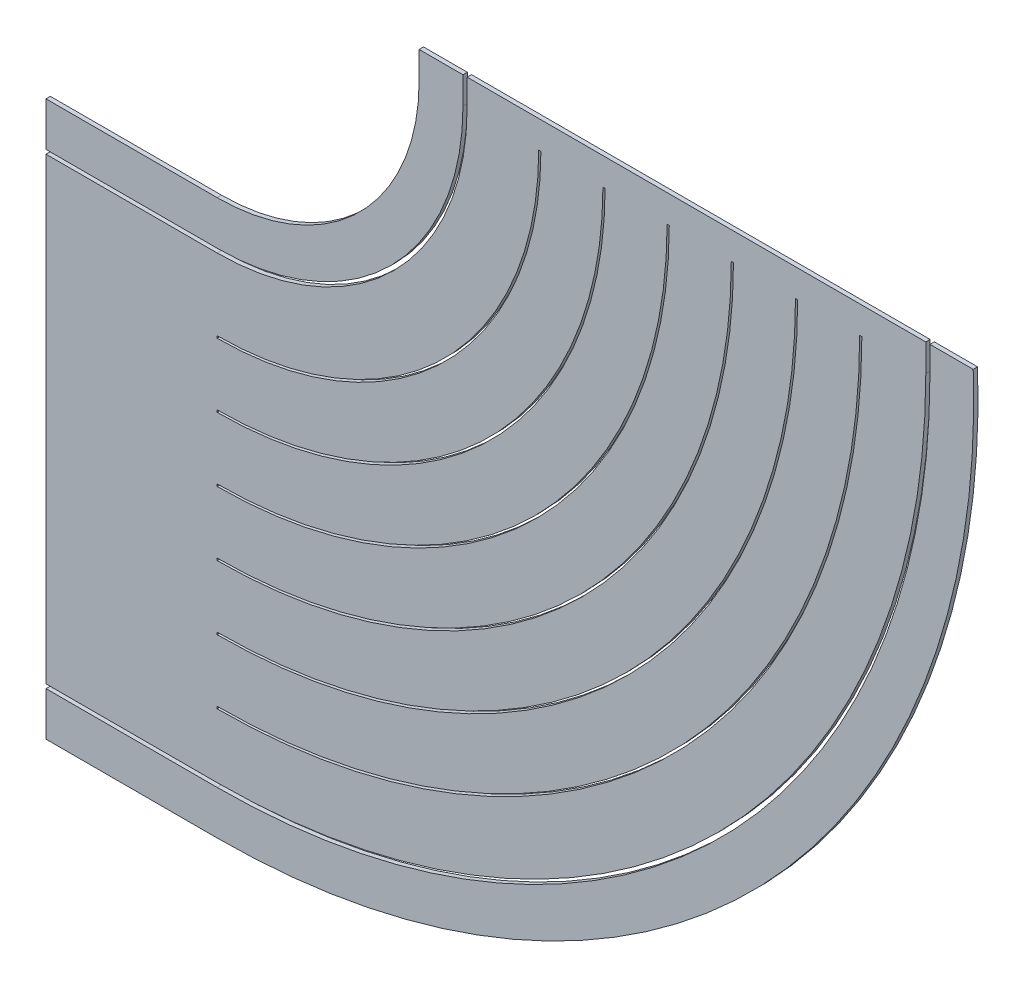
SolidWorks part; units mm, degrees
ref_plane "Front Plane" through (0, 0, 0) normal (0, 0, 1) x (1, 0, 0)
ref_plane "Top Plane" through (0, 0, 0) normal (0, 1, 0) x (1, 0, 0)
ref_plane "Right Plane" through (0, 0, 0) normal (1, 0, 0) x (0, 0, -1)
sketch "Sketch1" plane through (0, 0, 0) normal (0, 0, 1) x (1, 0, 0)
  line L2 (1495, -4410) -> (2304.2758, -4410)
  line L3 (1200, -4745) -> (950, -4745)
  line L4 (2302.7806, -4380) -> (1486.5746, -4380)
  line L5 (1130, -4736.5746) -> (1130, -5552.7806)
  line L8 (1495, -4450) -> (1495, -4410)
  line L10 (950, -5555) -> (950, -4745)
  line L12 (950, -4815) -> (950, -4809) construction
  line L17 (1565, -4410) -> (1559, -4410)
  line L18 (1200, -4809) -> (950, -4809)
  line L19 (950, -4809) -> (950, -4815)
  line L20 (950, -4815) -> (1200, -4815)
  line L21 (1565, -4410) -> (1559, -4410)
  line L22 (1200, -4809) -> (950, -4809)
  line L23 (950, -4809) -> (950, -4815)
  line L24 (950, -4815) -> (1200, -4815)
  line L47 (1565, -4450) -> (1565, -4410)
  line L48 (1565, -4450) -> (1565, -4410)
  line L49 (1559, -4410) -> (1559, -4450)
  line L50 (1559, -4410) -> (1559, -4450)
  line L183 (1200, -5555) -> (950, -5555)
  line L660 (1200, -4919.65) -> (1200, -4922.85)
  line L661 (1200, -5013.4) -> (1200, -5016.6)
  line L662 (1200, -5107.15) -> (1200, -5110.35)
  line L663 (1200, -5200.9) -> (1200, -5204.1)
  line L664 (1200, -5294.65) -> (1200, -5297.85)
  line L665 (1200, -5388.4) -> (1200, -5391.6)
  line L666 (1668.75, -4450) -> (2142.5, -4450)
  line L959 (1200, -5485) -> (950, -5485) construction
  line L960 (1200, -5491) -> (950, -5491) construction
  line L961 (1200, -5485) -> (950, -5485)
  line L962 (1200, -5491) -> (950, -5491)
  line L963 (2235, -4450) -> (2235, -4410)
  line L964 (2235, -4410) -> (2241, -4410)
  line L965 (2241, -4410) -> (2241, -4450)
  arc A2 (1200, -4745) -> (1495, -4450) centre (1200, -4450) ccw
  arc A4 (1130, -5552.7806) -> (2302.7806, -4380) centre (1200, -4450) ccw
  arc A5 (1130, -4736.5746) -> (1486.5746, -4380) centre (1200, -4450) ccw
  arc A6 (1200, -5555) -> (2304.2758, -4410) centre (1200, -4450) ccw
  arc A7 (1200, -4745) -> (1495, -4450) centre (1200, -4450) ccw
  arc A9 (1200, -4815) -> (1565, -4450) centre (1200, -4450) ccw
  arc A10 (1200, -4809) -> (1559, -4450) centre (1200, -4450) ccw
  arc A11 (1200, -4815) -> (1565, -4450) centre (1200, -4450) ccw
  arc A12 (1200, -4809) -> (1559, -4450) centre (1200, -4450) ccw
  arc A149 (1200, -5392.5) -> (2142.5, -4450) centre (1200, -4450) ccw construction
  arc A150 (1200, -5387.5) -> (2137.5, -4450) centre (1200, -4450) ccw construction
  arc A151 (1200, -5298.75) -> (2048.75, -4450) centre (1200, -4450) ccw construction
  arc A152 (1200, -5293.75) -> (2043.75, -4450) centre (1200, -4450) ccw construction
  arc A153 (1200, -5205) -> (1955, -4450) centre (1200, -4450) ccw construction
  arc A154 (1200, -5200) -> (1950, -4450) centre (1200, -4450) ccw construction
  arc A155 (1200, -5111.25) -> (1861.25, -4450) centre (1200, -4450) ccw construction
  arc A156 (1200, -5106.25) -> (1856.25, -4450) centre (1200, -4450) ccw construction
  arc A157 (1200, -5017.5) -> (1767.5, -4450) centre (1200, -4450) ccw construction
  arc A158 (1200, -5012.5) -> (1762.5, -4450) centre (1200, -4450) ccw construction
  arc A159 (1200, -4923.75) -> (1673.75, -4450) centre (1200, -4450) ccw construction
  arc A160 (1200, -4918.75) -> (1668.75, -4450) centre (1200, -4450) ccw construction
  arc A193 (1200, -5392.5) -> (2142.5, -4450) centre (1200, -4450) ccw construction
  arc A194 (1200, -5387.5) -> (2137.5, -4450) centre (1200, -4450) ccw construction
  arc A195 (1200, -5298.75) -> (2048.75, -4450) centre (1200, -4450) ccw construction
  arc A196 (1200, -5293.75) -> (2043.75, -4450) centre (1200, -4450) ccw construction
  arc A197 (1200, -5205) -> (1955, -4450) centre (1200, -4450) ccw construction
  arc A198 (1200, -5200) -> (1950, -4450) centre (1200, -4450) ccw construction
  arc A199 (1200, -5111.25) -> (1861.25, -4450) centre (1200, -4450) ccw construction
  arc A200 (1200, -5106.25) -> (1856.25, -4450) centre (1200, -4450) ccw construction
  arc A201 (1200, -5017.5) -> (1767.5, -4450) centre (1200, -4450) ccw construction
  arc A202 (1200, -5012.5) -> (1762.5, -4450) centre (1200, -4450) ccw construction
  arc A203 (1200, -4923.75) -> (1673.75, -4450) centre (1200, -4450) ccw construction
  arc A204 (1200, -4918.75) -> (1668.75, -4450) centre (1200, -4450) ccw construction
  arc A671 (1200, -4921.25) -> (1671.25, -4450) centre (1200, -4450) ccw construction
  arc A672 (1200, -5015) -> (1765, -4450) centre (1200, -4450) ccw construction
  arc A673 (1200, -5108.75) -> (1858.75, -4450) centre (1200, -4450) ccw construction
  arc A674 (1200, -5202.5) -> (1952.5, -4450) centre (1200, -4450) ccw construction
  arc A675 (1200, -5296.25) -> (2046.25, -4450) centre (1200, -4450) ccw construction
  arc A676 (1200, -5390) -> (2140, -4450) centre (1200, -4450) ccw construction
  arc A677 (1200, -4922.85) -> (1672.85, -4450) centre (1200, -4450) ccw
  arc A678 (1200, -5016.6) -> (1766.6, -4450) centre (1200, -4450) ccw
  arc A679 (1200, -5110.35) -> (1860.35, -4450) centre (1200, -4450) ccw
  arc A680 (1200, -5204.1) -> (1954.1, -4450) centre (1200, -4450) ccw
  arc A681 (1200, -5297.85) -> (2047.85, -4450) centre (1200, -4450) ccw
  arc A682 (1200, -5391.6) -> (2141.6, -4450) centre (1200, -4450) ccw
  arc A683 (1200, -4919.65) -> (1669.65, -4450) centre (1200, -4450) ccw
  arc A684 (1200, -5013.4) -> (1763.4, -4450) centre (1200, -4450) ccw
  arc A685 (1200, -5107.15) -> (1857.15, -4450) centre (1200, -4450) ccw
  arc A686 (1200, -5200.9) -> (1950.9, -4450) centre (1200, -4450) ccw
  arc A687 (1200, -5294.65) -> (2044.65, -4450) centre (1200, -4450) ccw
  arc A688 (1200, -5388.4) -> (2138.4, -4450) centre (1200, -4450) ccw
  arc A981 (1200, -5485) -> (2235, -4450) centre (1200, -4450) ccw construction
  arc A982 (1200, -5491) -> (2241, -4450) centre (1200, -4450) ccw construction
  arc A983 (1200, -5485) -> (2235, -4450) centre (1200, -4450) ccw
  arc A984 (1200, -5491) -> (2241, -4450) centre (1200, -4450) ccw
  dimension "D3" = 2.5
  dimension "D1" = 70
  dimension "D2" = 0
  dimension "D4" = 1.6
  dimension "D5" = 1.6
extrude "Boss-Extrude1" add sketch "Sketch1" along normal blind 6.35
